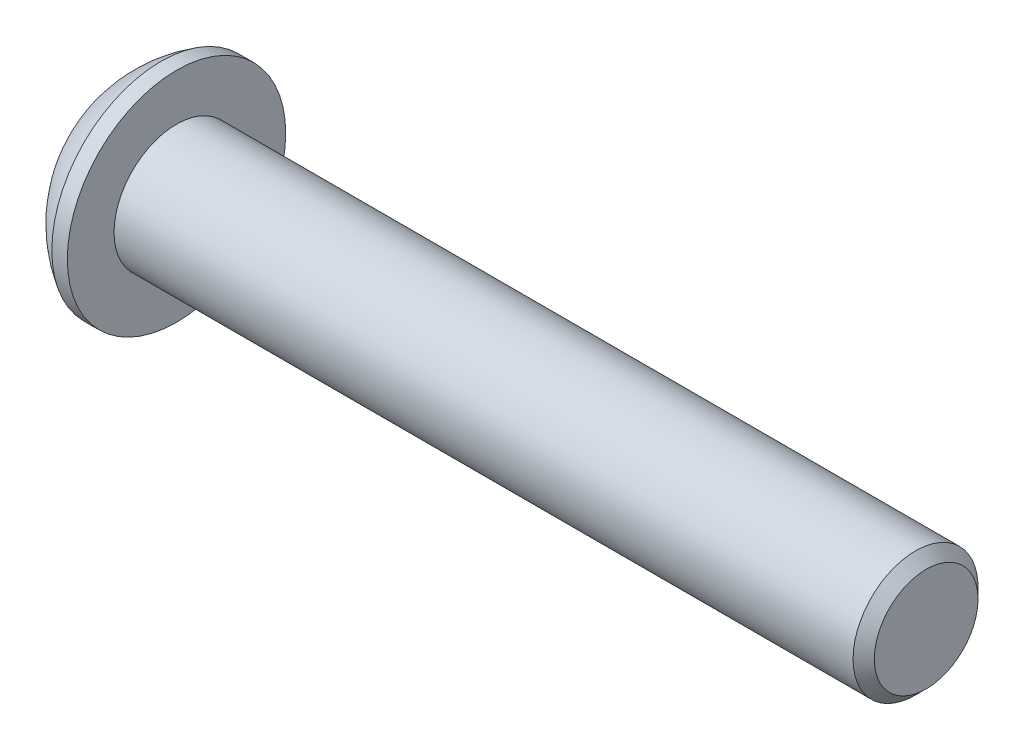
SolidWorks part; units mm, degrees
ref_plane "Plane1" through (0, 0, 0) normal (0, 0, 1) x (1, 0, 0)
ref_plane "Plane2" through (0, 0, 0) normal (0, 1, 0) x (1, 0, 0)
ref_plane "Plane3" through (0, 0, 0) normal (1, 0, 0) x (0, 0, -1)
sketch "BodySke" plane through (0, 0, 0) normal (0, 0, 1) x (1, 0, 0)
  line L0 (41.4528, 0) -> (41.4528, 2.634)
  line L1 (40.9118, 3.175) -> (3.3528, 3.175)
  line L2 (3.3528, 3.175) -> (3.3528, 5.5499)
  line L3 (3.3528, 5.5499) -> (2.5654, 5.5499)
  line L4 (0, 0) -> (101.6, 0) construction
  line L5 (3.3528, -5.5499) -> (2.5654, -5.5499) construction
  line L6 (55.6768, -3.175) -> (3.3528, -3.175) construction
  line L7 (41.4528, 0) -> (0, 0)
  line L8 (0, 2.775) -> (0, -2.775) construction
  line L9 (0, 0) -> (0, 2.775)
  line L10 (41.4528, 2.634) -> (40.9118, 3.175)
  line L11 (41.4528, -2.634) -> (40.9118, -3.175) construction
  line L12 (4.2596, 9.525) -> (4.2596, -3.175) construction
  line L13 (3.3528, 9.525) -> (3.3528, -3.175) construction
  arc A1 (0, 2.775) -> (2.5654, 5.5499) centre (5.7851, 0) cw
  dimension "Diameter" = 6.35
  dimension "Length" = 38.1
  dimension "Head_dia" = 11.0998
  dimension "D1" = 5.5499
  dimension "Head_ht" = 3.3528
  dimension "Head_side_ht" = 0.7874
  dimension "Minor_dia" = 5.268
  dimension "Body_ch_ang" = 45
  dimension "Advance" = 0.9068
  dimension "Thread_nom" = 38.1
revolve "BaseBody" add sketch "BodySke" angle 360 about L4
cosmetic thread "ThreadCosmetic" [suppressed] parameters "Thread_length"=37.1932, "Thread_minor"=5.268
sketch "Sketch2" plane through (0, 0, 0) normal (0, 0, 1) x (1, 0, 0)
  line L0 (0, 1.9812) -> (2.2098, 1.9812)
  line L1 (2.2098, 1.9812) -> (3.3536, 0)
  line L3 (3.3536, 0) -> (0, 0)
  line L4 (0, 0) -> (0, 1.9812)
  line L5 (0, -1.9812) -> (2.2098, -1.9812) construction
  line L6 (0, 0) -> (47.625, 0) construction
  dimension "D2" = 60
  dimension "PreBroach_depth" = 2.2098
  dimension "PreBroach_dia" = 3.9624
revolve "PreBroach" cut sketch "Sketch2" angle 360 about L6
sketch "Sketch3" plane through (0, 0, 0) normal (1, 0, 0) x (0, 0, -1)
  line L0 (-1.9812, -1.1438) -> (-1.9812, 1.1438)
  line L1 (-1.9812, 1.1438) -> (0, 2.2877)
  line L2 (0, 2.2877) -> (1.9812, 1.1438)
  line L3 (1.9812, 1.1438) -> (1.9812, -1.1438)
  line L4 (1.9812, -1.1438) -> (0, -2.2877)
  line L5 (0, -2.2877) -> (-1.9812, -1.1438)
  dimension "Hex_size" = 3.9624
  dimension "D3" = 3.9624
  dimension "D1" = 1.9812
  dimension "D2" = 1.9812
extrude "Hex" cut sketch "Sketch3" along normal blind 2.2098
sketch "Sketch4" plane through (0, 9.525, 0) normal (1, 0, 0) x (0, 0, -1)
  line L0 (0, -9.525) -> (2.3876, -9.525)
  line L1 (0, -9.525) -> (6.1484, -5.9752) construction
  line L2 (0, -9.525) -> (1.1938, -7.4573)
  line L3 (1.9883, -8.949) -> (2.2704, -8.7861)
  line L4 (1.493, -8.0911) -> (1.7751, -7.9282)
  arc A0 (1.9883, -8.949) -> (1.493, -8.0911) centre (0, -9.525) ccw
  arc A1 (2.3876, -9.525) -> (2.2704, -8.7861) centre (0, -9.525) ccw
  arc A2 (1.1938, -7.4573) -> (1.7751, -7.9282) centre (0, -9.525) cw
  dimension "Spline_n_dim" = 4.1402
  dimension "Spline_m_dim" = 4.7752
  dimension "D1" = 30
  dimension "D2" = 60
  dimension "Spline_p_dim" = 0.9906
  dimension "D3" = 0.4953
extrude "Spline" [suppressed] cut sketch "Sketch4" along normal blind 2.2098
pattern_circular "CirPattern1" [suppressed] count 6 every 60 about axis through (0, 0, 0) along (1, 0, 0)
sketch "ThdSchSke" plane through (0, 0, 0) normal (0, 0, 1) x (1, 0, 0)
  line L0 (4.2596, -2.634) -> (3.8808, -3.175)
  line L1 (4.2596, -2.634) -> (4.6384, -3.175)
  line L2 (4.6384, -3.175) -> (4.6384, -3.9688)
  line L3 (-3.175, 0) -> (5.1513, 0) construction
  line L5 (4.6384, -3.9688) -> (3.8808, -3.9688)
  line L6 (3.8808, -3.9688) -> (3.8808, -3.175)
  dimension "Diameter" = 6.35
  dimension "Thread_minor" = 5.268
  dimension "SideAngle" = 55
  dimension "VeeAngle" = 70
  dimension "Overcut" = 7.9375
  dimension "Start" = 4.2596
revolve "ThreadSchematic" [suppressed] cut sketch "ThdSchSke" angle 360 about L3
pattern_linear "ThdSchPat" [suppressed]
equation "\"D1@BodySke\" = \"Head_dia@BodySke\" * .5"
equation "\"Thread_minor@ThreadCosmetic\" = \"Minor_dia@BodySke\""
equation "\"D1@Sketch3\" = \"Hex_size@Sketch3\" / 2"
equation "\"D2@Sketch3\" = \"D1@Sketch3\""
equation "\"D3@Sketch3\" = \"Hex_size@Sketch3\""
equation "\"D3@Sketch4\" = \"Spline_p_dim@Sketch4\" / 2"
equation "\"D1@Sketch4\" = \"D2@Sketch4\" / 2"
equation "\"Thread_length@ThreadCosmetic\" = ((sgn( (\"Length@BodySke\" - \"Advance@BodySke\" ) - \"Thread_nom@BodySke\" )-1)*( (\"Length@BodySke\" - \"Advance@BodySke\" ) - \"Thread_nom@BodySke\" ))/-2+ \"Thread_nom@BodySke\""
equation "\"Thread_minor@ThdSchSke\" = \"Minor_dia@BodySke\""
equation "\"Diameter@ThdSchSke\" = \"Diameter@BodySke\""
equation "\"Overcut@ThdSchSke\" = \"Diameter@BodySke\" * 1.25"
equation "\"Start@ThdSchSke\" = \"Head_ht@BodySke\" + \"Length@BodySke\" - \"Thread_length@ThreadCosmetic\"  '---Non-countersunk---"
equation "\"Num_threads@ThdSchPat\" = int( \"Thread_length@ThreadCosmetic\" / \"Advance@BodySke\" + 0.999 )  + 1"
equation "\"Advance@ThdSchPat\" = \"Thread_length@ThreadCosmetic\" /  (\"Num_threads@ThdSchPat\" - 1) 'relax it"
equation "\"Num_threads@ThdSchPat\" = \"Num_threads@ThdSchPat\" - sgn( \"Num_threads@ThdSchPat\" - 1) '---chamfered tips only---"
